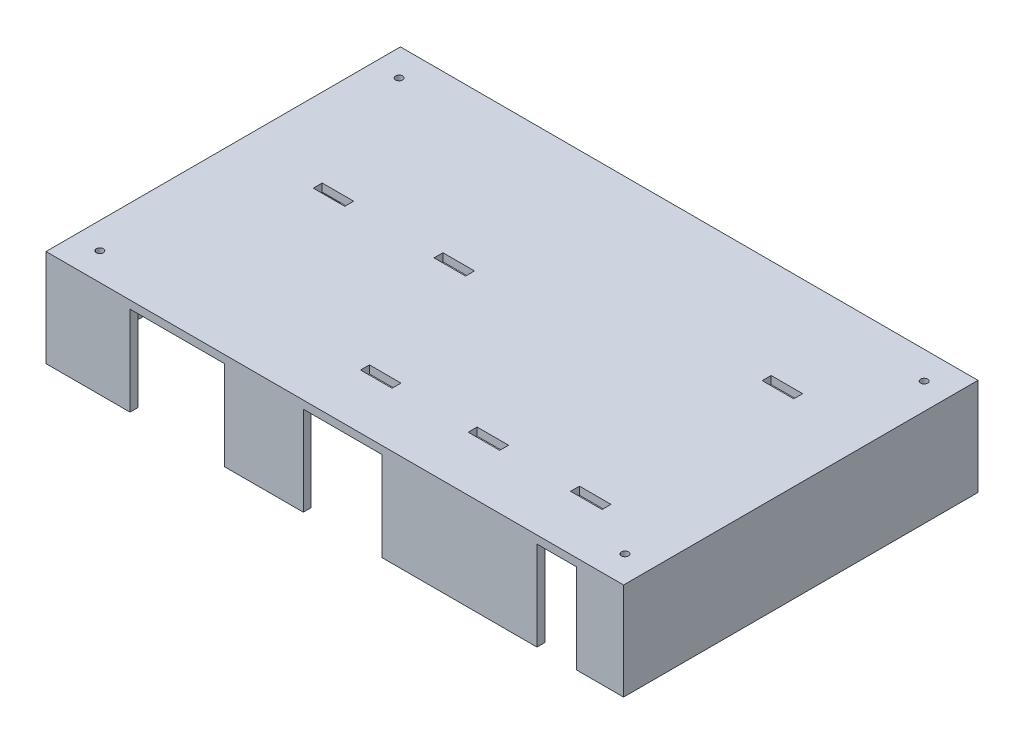
SolidWorks part; units mm, degrees
ref_plane "前视基准面" through (0, 0, 0) normal (0, 0, 1) x (1, 0, 0)
ref_plane "上视基准面" through (0, 0, 0) normal (0, 1, 0) x (1, 0, 0)
ref_plane "右视基准面" through (0, 0, 0) normal (1, 0, 0) x (0, 0, -1)
other "Configuration Table"
sketch "草图1" plane through (0, 0, 0) normal (0, 1, 0) x (1, 0, 0)
  line L1 (-110, -67.5) -> (110, -67.5)
  line L2 (-110, -67.5) -> (-110, 67.5)
  line L3 (-110, 67.5) -> (110, 67.5)
  line L4 (110, -67.5) -> (110, 67.5)
extrude "Base_Floor_3mm" add sketch "草图1" against normal blind 3
sketch "草图2" plane through (0, 0, 0) normal (0, 1, 0) x (1, 0, 0)
  line L0 (-110, 67.5) -> (-110, -67.5) construction
  line L1 (-110, 64.5) -> (110, 64.5)
  line L2 (-110, 64.5) -> (-110, 67.5)
  line L3 (-110, 67.5) -> (110, 67.5)
  line L4 (110, 64.5) -> (110, 67.5)
extrude "Back_Wall" add sketch "草图2" against normal blind 37
sketch "草图3" plane through (0, 0, 0) normal (0, 1, 0) x (1, 0, 0)
  line L1 (-110, -67.5) -> (-107, -67.5)
  line L2 (-110, -67.5) -> (-110, 64.5)
  line L3 (-110, 64.5) -> (-107, 64.5)
  line L4 (-107, -67.5) -> (-107, 64.5)
extrude "Left_Wall" add sketch "草图3" against normal blind 37
sketch "草图4" plane through (0, 0, 0) normal (0, 1, 0) x (1, 0, 0)
  line L0 (-110, -67.5) -> (110, -67.5) construction
  line L1 (107, -67.5) -> (110, -67.5)
  line L2 (107, -67.5) -> (107, 64.5)
  line L3 (107, 64.5) -> (110, 64.5)
  line L4 (110, -67.5) -> (110, 64.5)
  line L5 (110, -67.5) -> (110, 67.5) construction
extrude "Right_Wall" add sketch "草图4" against normal blind 37
sketch "草图5" plane through (0, 0, 0) normal (0, 1, 0) x (1, 0, 0)
  line L1 (-110, -67.5) -> (-78, -67.5)
  line L2 (-110, -67.5) -> (-110, -64.5)
  line L3 (-110, -64.5) -> (-78, -64.5)
  line L4 (-78, -67.5) -> (-78, -64.5)
extrude "Front_Left_Wall" add sketch "草图5" against normal blind 37
sketch "草图6" plane through (0, 0, 0) normal (0, 1, 0) x (1, 0, 0)
  line L0 (-110, -67.5) -> (110, -67.5) construction
  line L1 (-42, -67.5) -> (-12, -67.5)
  line L2 (-42, -67.5) -> (-42, -64.5)
  line L3 (-42, -64.5) -> (-12, -64.5)
  line L4 (-12, -67.5) -> (-12, -64.5)
extrude "Front_Camera_Bridge" add sketch "草图6" against normal blind 37
sketch "草图7" plane through (0, 0, 0) normal (0, 1, 0) x (1, 0, 0)
  line L0 (-110, -67.5) -> (110, -67.5) construction
  line L1 (18, -67.5) -> (77, -67.5)
  line L2 (18, -67.5) -> (18, -64.5)
  line L3 (18, -64.5) -> (77, -64.5)
  line L4 (77, -67.5) -> (77, -64.5)
extrude "Front_SR04_Bridge" add sketch "草图7" against normal blind 37
sketch "草图8" plane through (0, 0, 0) normal (0, 1, 0) x (1, 0, 0)
  line L0 (-110, -67.5) -> (110, -67.5) construction
  line L1 (92, -67.5) -> (110, -67.5)
  line L2 (92, -67.5) -> (92, -64.5)
  line L3 (92, -64.5) -> (110, -64.5)
  line L4 (110, -67.5) -> (110, -64.5)
  line L5 (110, -67.5) -> (110, 67.5) construction
extrude "Front_Right_Wall" add sketch "草图8" against normal blind 37
sketch "草图9" plane through (0, 0, 0) normal (0, 1, 0) x (1, 0, 0)
  circle A0 centre (-100, -57) radius 5
extrude "Lid_Boss_1" add sketch "草图9" against normal blind 30
sketch "草图10" plane through (0, 0, 0) normal (0, 1, 0) x (1, 0, 0)
  circle A0 centre (-100, -57) radius 1.35
extrude "Lid_Boss_1_Pilot" cut sketch "草图10" against normal blind 34
sketch "草图11" plane through (0, 0, 0) normal (0, 1, 0) x (1, 0, 0)
  circle A0 centre (100, -57) radius 5
extrude "Lid_Boss_2" add sketch "草图11" against normal blind 30
sketch "草图12" plane through (0, 0, 0) normal (0, 1, 0) x (1, 0, 0)
  circle A0 centre (100, -57) radius 1.35
extrude "Lid_Boss_2_Pilot" cut sketch "草图12" against normal blind 34
sketch "草图13" plane through (0, 0, 0) normal (0, 1, 0) x (1, 0, 0)
  circle A0 centre (-100, 57) radius 5
extrude "Lid_Boss_3" add sketch "草图13" against normal blind 30
sketch "草图14" plane through (0, 0, 0) normal (0, 1, 0) x (1, 0, 0)
  circle A0 centre (-100, 57) radius 1.35
extrude "Lid_Boss_3_Pilot" cut sketch "草图14" against normal blind 34
sketch "草图15" plane through (0, 0, 0) normal (0, 1, 0) x (1, 0, 0)
  circle A0 centre (100, 57) radius 5
extrude "Lid_Boss_4" add sketch "草图15" against normal blind 30
sketch "草图16" plane through (0, 0, 0) normal (0, 1, 0) x (1, 0, 0)
  circle A0 centre (100, 57) radius 1.35
extrude "Lid_Boss_4_Pilot" cut sketch "草图16" against normal blind 34
sketch "草图17" plane through (0, 0, 0) normal (0, 1, 0) x (1, 0, 0)
  circle A0 centre (-93, 18) radius 1.6
extrude "P4_NANO_Peg_1" add sketch "草图17" against normal blind 7
sketch "草图18" plane through (0, 0, 0) normal (0, 1, 0) x (1, 0, 0)
  circle A0 centre (-48, 18) radius 1.6
extrude "P4_NANO_Peg_2" add sketch "草图18" against normal blind 7
sketch "草图19" plane through (0, 0, 0) normal (0, 1, 0) x (1, 0, 0)
  circle A0 centre (-93, 63) radius 1.6
extrude "P4_NANO_Peg_3" add sketch "草图19" against normal blind 7
sketch "草图20" plane through (0, 0, 0) normal (0, 1, 0) x (1, 0, 0)
  circle A0 centre (-48, 63) radius 1.6
extrude "P4_NANO_Peg_4" add sketch "草图20" against normal blind 7
sketch "草图21" plane through (0, 0, 0) normal (0, 1, 0) x (1, 0, 0)
  circle A0 centre (0, -30) radius 1.6
extrude "Mega_Peg_1" add sketch "草图21" against normal blind 7
sketch "草图22" plane through (0, 0, 0) normal (0, 1, 0) x (1, 0, 0)
  circle A0 centre (96, -30) radius 1.6
extrude "Mega_Peg_2" add sketch "草图22" against normal blind 7
sketch "草图23" plane through (0, 0, 0) normal (0, 1, 0) x (1, 0, 0)
  circle A0 centre (0, 12) radius 1.6
extrude "Mega_Peg_3" add sketch "草图23" against normal blind 7
sketch "草图24" plane through (0, 0, 0) normal (0, 1, 0) x (1, 0, 0)
  circle A0 centre (96, 12) radius 1.6
extrude "Mega_Peg_4" add sketch "草图24" against normal blind 7
sketch "草图25" plane through (0, 0, 0) normal (0, 1, 0) x (1, 0, 0)
  line L1 (-80, 4.3) -> (-68, 4.3)
  line L2 (-80, 4.3) -> (-80, 7.7)
  line L3 (-80, 7.7) -> (-68, 7.7)
  line L4 (-68, 4.3) -> (-68, 7.7)
extrude "Cable_Tie_Slot_1" cut sketch "草图25" against normal blind 4
sketch "草图26" plane through (0, 0, 0) normal (0, 1, 0) x (1, 0, 0)
  line L1 (-34, 4.3) -> (-22, 4.3)
  line L2 (-34, 4.3) -> (-34, 7.7)
  line L3 (-34, 7.7) -> (-22, 7.7)
  line L4 (-22, 4.3) -> (-22, 7.7)
extrude "Cable_Tie_Slot_2" cut sketch "草图26" against normal blind 4
sketch "草图27" plane through (0, 0, 0) normal (0, 1, 0) x (1, 0, 0)
  line L1 (-11, -46.7) -> (1, -46.7)
  line L2 (-11, -46.7) -> (-11, -43.3)
  line L3 (-11, -43.3) -> (1, -43.3)
  line L4 (1, -46.7) -> (1, -43.3)
extrude "Cable_Tie_Slot_3" cut sketch "草图27" against normal blind 4
sketch "草图28" plane through (0, 0, 0) normal (0, 1, 0) x (1, 0, 0)
  line L1 (30, -46.7) -> (42, -46.7)
  line L2 (30, -46.7) -> (30, -43.3)
  line L3 (30, -43.3) -> (42, -43.3)
  line L4 (42, -46.7) -> (42, -43.3)
extrude "Cable_Tie_Slot_4" cut sketch "草图28" against normal blind 4
sketch "草图29" plane through (0, 0, 0) normal (0, 1, 0) x (1, 0, 0)
  line L1 (69, -46.7) -> (81, -46.7)
  line L2 (69, -46.7) -> (69, -43.3)
  line L3 (69, -43.3) -> (81, -43.3)
  line L4 (81, -46.7) -> (81, -43.3)
extrude "Cable_Tie_Slot_5" cut sketch "草图29" against normal blind 4
sketch "草图30" plane through (0, 0, 0) normal (0, 1, 0) x (1, 0, 0)
  line L1 (69, 26.3) -> (81, 26.3)
  line L2 (69, 26.3) -> (69, 29.7)
  line L3 (69, 29.7) -> (81, 29.7)
  line L4 (81, 26.3) -> (81, 29.7)
extrude "Cable_Tie_Slot_6" cut sketch "草图30" against normal blind 4
sketch "草图31" plane through (0, 0, 0) normal (0, 1, 0) x (1, 0, 0)
  line L1 (28, 31) -> (95, 31)
  line L2 (28, 31) -> (28, 34)
  line L3 (28, 34) -> (95, 34)
  line L4 (95, 31) -> (95, 34)
extrude "Adjustable_Sensor_Rail_1" add sketch "草图31" against normal blind 4
sketch "草图32" plane through (0, 0, 0) normal (0, 1, 0) x (1, 0, 0)
  line L1 (28, 49) -> (95, 49)
  line L2 (28, 49) -> (28, 52)
  line L3 (28, 52) -> (95, 52)
  line L4 (95, 49) -> (95, 52)
extrude "Adjustable_Sensor_Rail_2" add sketch "草图32" against normal blind 4
